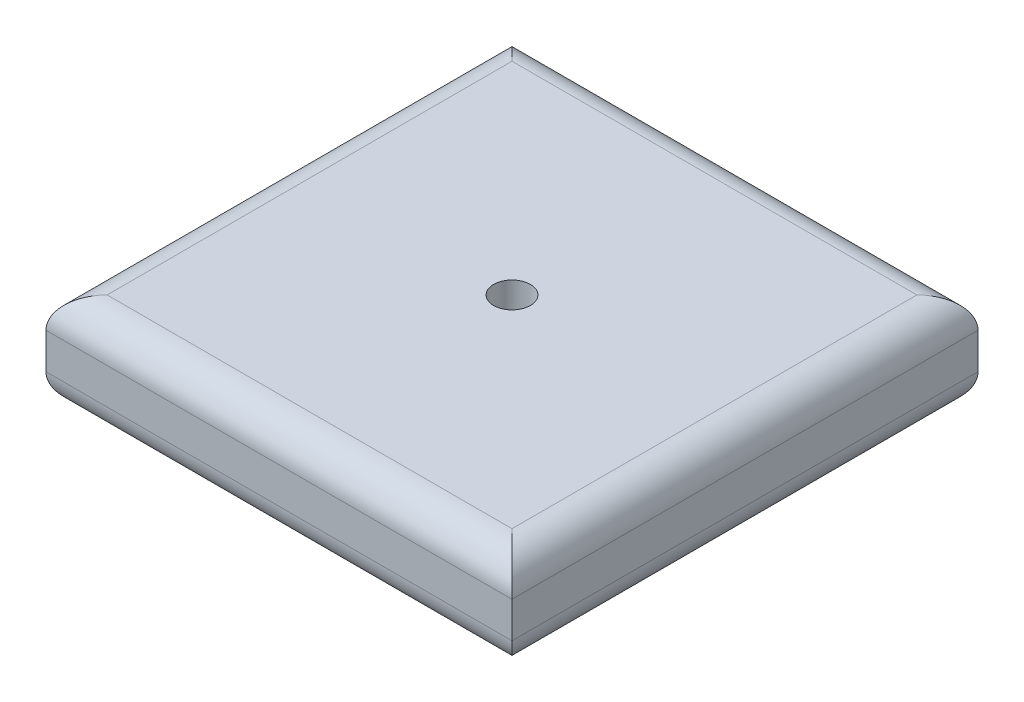
SolidWorks part; units mm, degrees
ref_plane "Front Plane" through (0, 0, 0) normal (0, 0, 1) x (1, 0, 0)
ref_plane "Top Plane" through (0, 0, 0) normal (0, 1, 0) x (1, 0, 0)
ref_plane "Right Plane" through (0, 0, 0) normal (1, 0, 0) x (0, 0, -1)
sketch "Sketch1" plane through (0, 0, 0) normal (0, 1, 0) x (1, 0, 0)
  line L1 (-33.753, 152.4) -> (118.647, 152.4)
  line L2 (-33.753, 152.4) -> (-33.753, 0)
  line L3 (-33.753, 0) -> (118.647, 0)
  line L4 (118.647, 152.4) -> (118.647, 0)
  dimension "D1" = 152.4
  dimension "D2" = 152.4
extrude "Boss-Extrude1" add sketch "Sketch1" along normal blind 31.75
sketch "Sketch2" plane through (0, 31.75, 0) normal (0, 1, 0) x (1, 0, 0)
  line L0 (-33.753, 152.4) -> (-33.753, 0) construction
  line L2 (-33.753, 0) -> (118.647, 0) construction
  circle A0 centre (42.447, 76.2) radius 6
  point P4 (0, 0)
  point P7 (0, 0)
  point P8 (0, 0)
  dimension "D2" = 12
  dimension "D1" = 76.2
  dimension "D3" = 76.2
extrude "Cut-Extrude1" cut sketch "Sketch2" against normal blind 15
fillet "Fillet1" radius 10 4 edges at (42.447, 31.75, -152.4) (-33.753, 31.75, -76.2) (42.447, 31.75, 0) (118.647, 31.75, -76.2)
fillet "Fillet2" radius 10 4 edges at (42.447, 0, -152.4) (-33.753, 0, -76.2) (42.447, 0, 0) (118.647, 0, -76.2)
